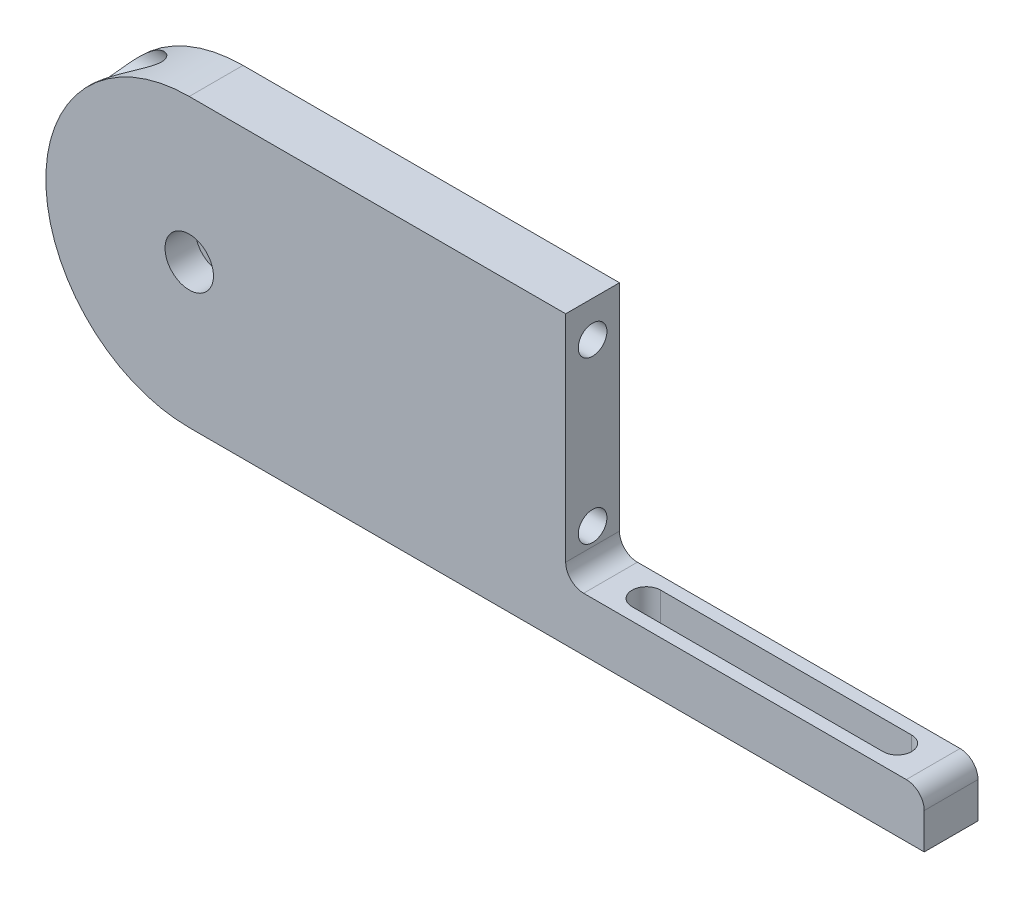
SolidWorks part; units mm, degrees
material "3.3549 (EN-AW 5182)"
ref_plane "Piano frontale" through (0, 0, 0) normal (0, 0, 1) x (1, 0, 0)
ref_plane "Piano superiore" through (0, 0, 0) normal (0, 1, 0) x (1, 0, 0)
ref_plane "Piano destro" through (0, 0, 0) normal (1, 0, 0) x (0, 0, -1)
sketch "Schizzo1" plane through (0, 0, 0) normal (0, 0, 1) x (1, 0, 0)
  line L0 (0, 0) -> (105, 0) construction
  line L1 (0, 40) -> (105, 40)
  line L3 (0, -40) -> (105, -40)
  line L4 (105, 40) -> (105, -40)
  arc A0 (0, 40) -> (0, -40) centre (0, 0) ccw
  dimension "D2" = 80
  dimension "D3" = 105
extrude "Estrusione1" add sketch "Schizzo1" along normal mid plane 15
sketch "Schizzo2" plane through (0, 0, 7.5) normal (0, 0, 1) x (1, 0, 0)
  circle A0 centre (0, 0) radius 4
  dimension "D1" = 8
extrude "Taglio-Estrusione1" cut sketch "Schizzo2" against normal blind 15
sketch "Schizzo4" plane through (0, 0, 7.5) normal (0, 0, 1) x (1, 0, 0)
  circle A0 centre (0, 0) radius 6.75
  dimension "D1" = 13.5
extrude "Taglio-Estrusione3" cut sketch "Schizzo4" against normal blind 8.5
sketch "Schizzo11" plane through (105, 0, 0) normal (1, 0, 0) x (0, 0, -1)
  line L0 (7.5, -40) -> (7.5, 40) construction
  line L1 (-7.5, -40) -> (7.5, -40)
  line L2 (-7.5, -40) -> (-7.5, -25)
  line L3 (-7.5, -25) -> (7.5, -25)
  line L4 (7.5, -40) -> (7.5, -25)
  dimension "D1" = 15
extrude "Estrusione3" add sketch "Schizzo11" along normal blind 100
fillet "Raccordo2" radius 5 2 edges at (205, -25, 0)
sketch "Schizzo13" plane through (105, 0, 0) normal (1, 0, 0) x (0, 0, -1)
  line L0 (0, 52.9681) -> (0, -49.039) construction
  line L1 (19.9286, 0) -> (-23.5945, 0) construction
  circle A0 centre (0, -15) radius 4
  circle A1 centre (0, 30) radius 4
  dimension "D2" = 8
  dimension "D3" = 8
  dimension "D1" = 15
  dimension "D4" = 30
extrude "Taglio-Estrusione4" cut sketch "Schizzo13" against normal through all
ref_plane "Piano1" through (85, 0, 0) normal (1, 0, 0) x (0, 0, -1)
sketch "Schizzo14" plane through (85, 0, 0) normal (1, 0, 0) x (0, 0, -1)
  circle A0 centre (0, 30) radius 7
  circle A1 centre (0, -15) radius 7
  dimension "D1" = 14
  dimension "D2" = 14
extrude "Taglio-Estrusione5" cut sketch "Schizzo14" against normal through all
sketch "Schizzo15" plane through (0, -40, 0) normal (0, -1, 0) x (1, 0, 0)
  line L0 (-47.8471, 0) -> (151.0204, 0) construction
  line L1 (205, 7.5) -> (205, -7.5) construction
  line L2 (120, 4) -> (190, 4)
  line L4 (120, -4) -> (190, -4)
  arc A0 (120, 4) -> (120, -4) centre (120, 0) ccw
  arc A1 (190, -4) -> (190, 4) centre (190, 0) ccw
  dimension "D1" = 15
  dimension "D2" = 70
  dimension "D3" = 8
extrude "Taglio-Estrusione6" cut sketch "Schizzo15" against normal blind 100
